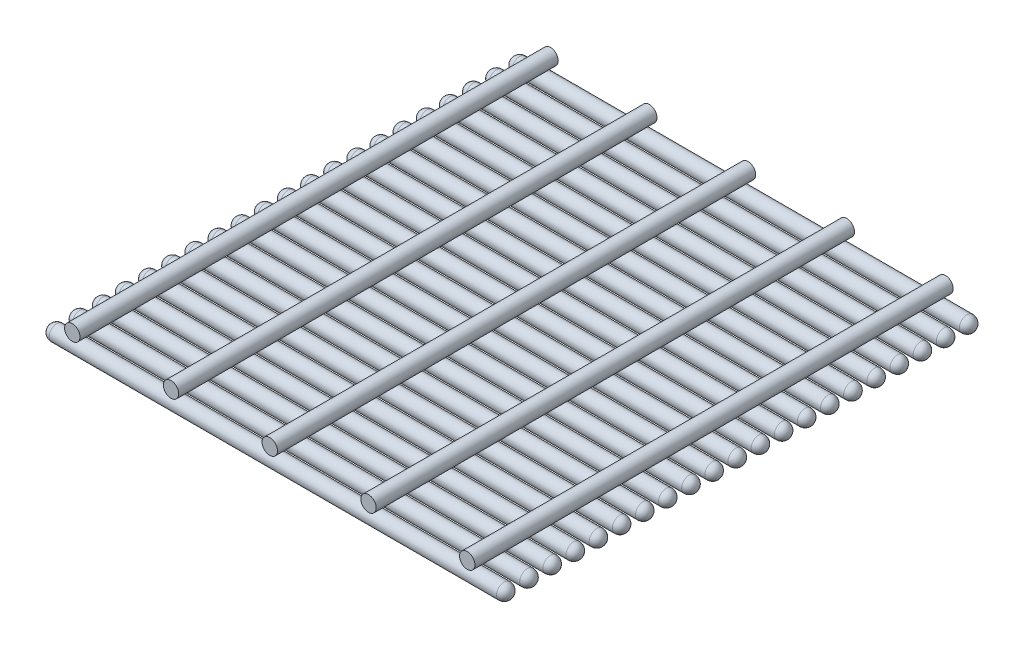
SolidWorks part; units mm, degrees
ref_plane "Plan de face" through (0, 0, 0) normal (0, 0, 1) x (1, 0, 0)
ref_plane "Plan de dessus" through (0, 0, 0) normal (0, 1, 0) x (1, 0, 0)
ref_plane "Plan de droite" through (0, 0, 0) normal (1, 0, 0) x (0, 0, -1)
sketch "Esquisse2" plane through (0, 0, 0) normal (1, 0, 0) x (0, 0, -1)
  circle A0 centre (0, 0) radius 2.5
  dimension "D1" = 5
extrude "Boss.-Extru.1" add sketch "Esquisse2" along normal blind 150
sketch "Esquisse3" plane through (150, 0, 0) normal (1, 0, 0) x (0, 0, -1)
  line L0 (0, 0) -> (150, 0)
fillet "Congé4" radius 2.5 1 edges at (0, 0, -2.5)
fillet "Congé5" radius 2.5 1 edges at (150, 0, -2.5)
pattern_linear "Répétition linéaire2" count 21 spacing 7.5 along (0, 0, -1) of bodies 101
sketch "Esquisse4" plane through (0, 0, 0) normal (0, 0, 1) x (1, 0, 0)
  line L0 (0, 0) -> (10, 0)
  line L1 (10, 0) -> (10, 5)
  circle A0 centre (10, 5) radius 2.5
  dimension "D1" = 5
extrude "Boss.-Extru.2" add sketch "Esquisse4" along normal blind 2.5 and the other way blind 152.5 separate body contours A0
pattern_linear "Répétition linéaire3" count 5 spacing 32 along (1, 0, 0) of bodies 142
